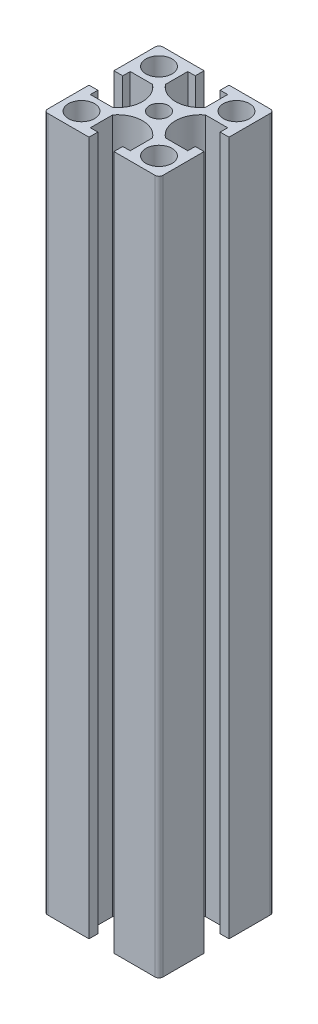
SolidWorks part; units mm, degrees
ref_plane "前视基准面" through (0, 0, 0) normal (0, 0, 1) x (1, 0, 0)
ref_plane "上视基准面" through (0, 0, 0) normal (0, 1, 0) x (1, 0, 0)
ref_plane "右视基准面" through (0, 0, 0) normal (1, 0, 0) x (0, 0, -1)
sketch "草图1" plane through (0, 0, 0) normal (0, 1, 0) x (1, 0, 0)
  line L0 (0, 19.2585) -> (0, -22.5636) construction
  line L1 (-14, 15) -> (-3.25, 15)
  line L2 (-15, 14) -> (-15, 3.25)
  line L3 (-14, -15) -> (-3.25, -15)
  line L4 (15, 14) -> (15, 3.25)
  line L5 (-15, 15) -> (15, -15) construction
  line L6 (-15, -15) -> (15, 15) construction
  line L7 (-24.4068, 0) -> (20.339, 0) construction
  line L8 (-3.25, 15) -> (-3.25, 12.7)
  line L9 (-3.25, 12.7) -> (-5.2, 12.7)
  line L10 (-5.2, 12.7) -> (-5.2, 6.9)
  line L11 (3.25, 15) -> (3.25, 12.7)
  line L12 (5.2, 12.7) -> (5.2, 6.9)
  line L13 (3.25, 12.7) -> (5.2, 12.7)
  line L14 (3.25, 15) -> (14, 15)
  line L15 (-15, -3.25) -> (-12.7, -3.25)
  line L16 (-12.7, -3.25) -> (-12.7, -5.2)
  line L17 (-12.7, -5.2) -> (-6.9, -5.2)
  line L18 (-12.7, 5.2) -> (-6.9, 5.2)
  line L19 (-12.7, 3.25) -> (-12.7, 5.2)
  line L20 (-15, 3.25) -> (-12.7, 3.25)
  line L21 (3.25, -15) -> (3.25, -12.7)
  line L22 (3.25, -12.7) -> (5.2, -12.7)
  line L23 (5.2, -12.7) -> (5.2, -6.9)
  line L24 (-5.2, -12.7) -> (-5.2, -6.9)
  line L25 (-3.25, -12.7) -> (-5.2, -12.7)
  line L26 (-3.25, -15) -> (-3.25, -12.7)
  line L27 (15, 3.25) -> (12.7, 3.25)
  line L28 (12.7, 3.25) -> (12.7, 5.2)
  line L29 (12.7, 5.2) -> (6.9, 5.2)
  line L30 (12.7, -5.2) -> (6.9, -5.2)
  line L31 (12.7, -3.25) -> (12.7, -5.2)
  line L32 (15, -3.25) -> (12.7, -3.25)
  line L33 (-15, -3.25) -> (-15, -14)
  line L34 (3.25, -15) -> (14, -15)
  line L35 (15, -3.25) -> (15, -14)
  arc A0 (14, 15) -> (15, 14) centre (14, 14) cw
  arc A1 (-15, -14) -> (-14, -15) centre (-14, -14) ccw
  arc A2 (-14, 15) -> (-15, 14) centre (-14, 14) ccw
  arc A3 (14, -15) -> (15, -14) centre (14, -14) ccw
  circle A4 centre (0, 0) radius 2.5
  circle A5 centre (-10.1, 10.1) radius 3.4
  circle A6 centre (10.1, 10.1) radius 3.4
  circle A7 centre (10.1, -10.1) radius 3.4
  circle A8 centre (-10.1, -10.1) radius 3.4
  arc A9 (-5.2, 6.9) -> (5.2, 6.9) centre (0, 10.8) ccw
  arc A10 (-6.9, -5.2) -> (-6.9, 5.2) centre (-10.8, 0) ccw
  arc A11 (5.2, -6.9) -> (-5.2, -6.9) centre (0, -10.8) ccw
  arc A12 (6.9, 5.2) -> (6.9, -5.2) centre (10.8, 0) ccw
  point P0 (0, 0)
  point P41 (0, 4.3)
  point P72 (0, 0)
  dimension "D3" = 1
  dimension "D4" = 5
  dimension "D7" = 10.7
  dimension "D10" = 6.8
  dimension "D9" = 6.5
  dimension "D1" = 30
  dimension "D2" = 30
  dimension "D5" = 20.2
  dimension "D6" = 20.2
  dimension "D8" = 6.5
  dimension "D11" = 2.3
  dimension "D12" = 10.4
  dimension "D13" = 10.8
  dimension "D14" = 4
extrude "凸台-拉伸1" add sketch "草图1" along normal blind 181
